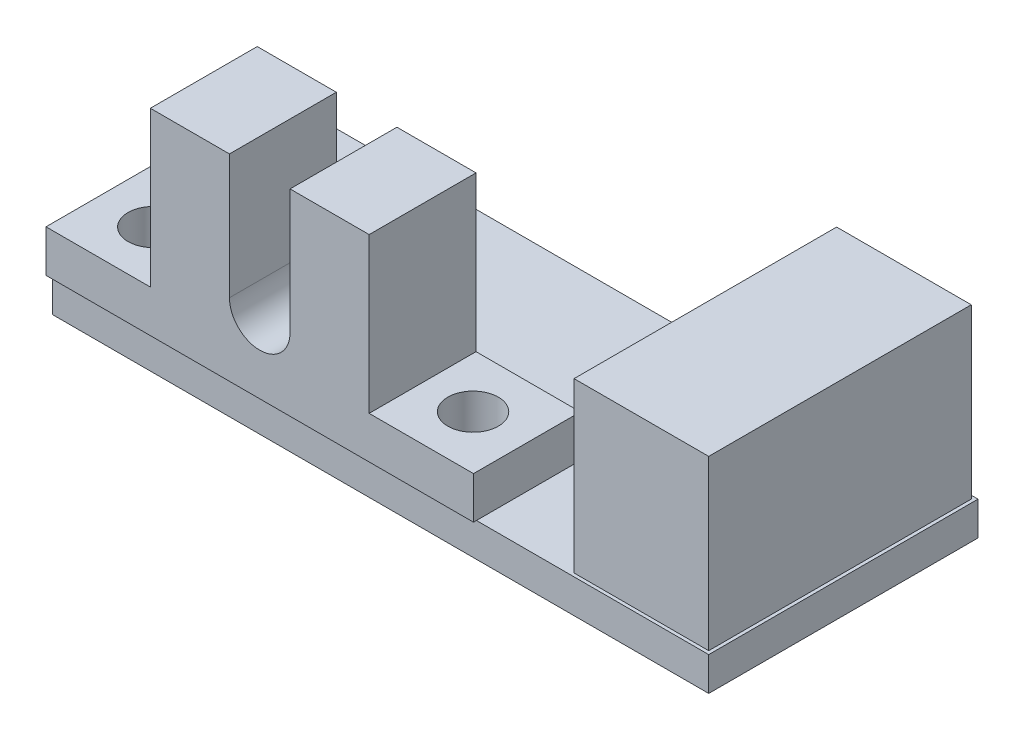
SolidWorks part; units mm, degrees
ref_plane "Front Plane" through (0, 0, 0) normal (0, 0, 1) x (1, 0, 0)
ref_plane "Top Plane" through (0, 0, 0) normal (0, 1, 0) x (1, 0, 0)
ref_plane "Right Plane" through (0, 0, 0) normal (1, 0, 0) x (0, 0, -1)
sketch "Sketch1" plane through (0, 0, 0) normal (0, 1, 0) x (1, 0, 0)
  line L0 (-19.5, 8) -> (19.5, -8) construction
  line L1 (-19.5, 8) -> (19.5, 8)
  line L2 (-19.5, 8) -> (-19.5, -8)
  line L3 (-19.5, -8) -> (19.5, -8)
  line L4 (19.5, 8) -> (19.5, -8)
  line L5 (-16.5, -5) -> (2.5, -5) construction
  circle A0 centre (-16.5, -5) radius 1.5
  circle A1 centre (2.5, -5) radius 1.5
  dimension "D4" = 3
  dimension "D1" = 39
  dimension "D2" = 16
  dimension "D3" = 19
  dimension "D5" = 3
  dimension "D6" = 3
extrude "Boss-Extrude1" add sketch "Sketch1" along normal blind 2
sketch "Sketch3" plane through (0, 2, 0) normal (0, 1, 0) x (1, 0, 0)
  line L0 (-19.7, -5) -> (-16.5, -5) construction
  line L1 (-19.7, -1.825) -> (5.7, -1.825)
  line L2 (-19.7, -1.825) -> (-19.7, -8.175)
  line L3 (-19.7, -8.175) -> (5.7, -8.175)
  line L4 (5.7, -1.825) -> (5.7, -8.175)
  line L5 (-16.5, -5) -> (2.5, -5) construction
  line L6 (-7, -5) -> (-7, -1.825) construction
  circle A0 centre (-16.5, -5) radius 1.5
  circle A1 centre (2.5, -5) radius 1.5
  circle A2 centre (2.5, -5) radius 1.5 construction
  dimension "D1" = 6.35
  dimension "D2" = 25.4
extrude "Boss-Extrude2" add sketch "Sketch3" along normal blind 2.5
sketch "Sketch4" plane through (0, 0, 8.175) normal (0, 0, 1) x (1, 0, 0)
  line L0 (-19.7, 4.5) -> (5.7, 4.5) construction
  line L1 (-13.5, 13.7) -> (-8.8, 13.7)
  line L2 (-13.5, 13.7) -> (-13.5, 4.5)
  line L3 (-13.5, 4.5) -> (-0.5, 4.5)
  line L4 (-0.5, 13.7) -> (-0.5, 4.5)
  line L5 (-7, 13.7) -> (-7, 2) construction
  line L6 (-19.7, 2) -> (5.7, 2) construction
  line L7 (-7, 13.7) -> (-7, 6.3) construction
  line L8 (-5.2, 13.7) -> (-5.2, 6.3)
  line L9 (-8.8, 13.7) -> (-8.8, 6.3)
  line L10 (-5.2, 13.7) -> (-0.5, 13.7)
  arc A1 (-8.8, 6.3) -> (-5.2, 6.3) centre (-7, 6.3) ccw
  point P12 (-7, 12.2834)
  line M3 (5.7, 4.5) -> (-19.7, 4.5)
  dimension "D1" = 13
  dimension "D2" = 9.2
  dimension "D3" = 3.6
extrude "Boss-Extrude3" add sketch "Sketch4" against normal up to surface (6.35 mm away) contours A1 L9 L1 L2 L3 | A1 L4 L10 L8 M3 up to face at (-9.5, 3, 1.825)
sketch "Sketch5" plane through (0, 2, 0) normal (0, 1, 0) x (1, 0, 0)
  line L1 (19.3, 7.8) -> (11.3, 7.8)
  line L2 (19.3, 7.8) -> (19.3, -7.8)
  line L3 (19.3, -7.8) -> (11.3, -7.8)
  line L4 (11.3, 7.8) -> (11.3, -7.8)
  line L9 (19.3, 0) -> (19.5, 0) construction
  line L10 (19.5, -8) -> (19.5, 8) construction
  line L11 (15.3, 7.8) -> (15.3, 8) construction
  line L12 (19.5, 8) -> (-19.5, 8) construction
  line L13 (15.3, -7.8) -> (15.3, -8) construction
  line L14 (5.7, -8) -> (19.5, -8) construction
  dimension "D1" = 8
  dimension "D2" = 0.2
extrude "Boss-Extrude4" add sketch "Sketch5" along normal offset from surface (10 mm away) 12 up to face at (-16.5, 0, 6.5)
